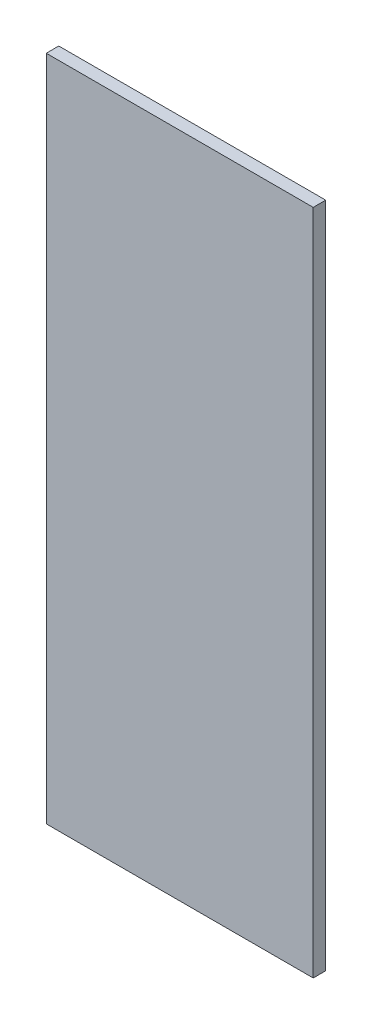
SolidWorks part; units mm, degrees
ref_plane "Plano frontal" through (0, 0, 0) normal (0, 0, 1) x (1, 0, 0)
ref_plane "Plano superior" through (0, 0, 0) normal (0, 1, 0) x (1, 0, 0)
ref_plane "Plano direito" through (0, 0, 0) normal (1, 0, 0) x (0, 0, -1)
sketch "Esboço1" plane through (0, 0, 0) normal (0, 0, 1) x (1, 0, 0)
  line L1 (-160, 400) -> (160, 400)
  line L2 (-160, 400) -> (-160, -400)
  line L3 (-160, -400) -> (160, -400)
  line L4 (160, 400) -> (160, -400)
  line L5 (-160, 400) -> (160, -400) construction
  line L6 (-160, -400) -> (160, 400) construction
  point P0 (0, 0)
  dimension "D1" = 320
  dimension "D2" = 800
extrude "Ressalto-extrusão1" add sketch "Esboço1" along normal blind 15
